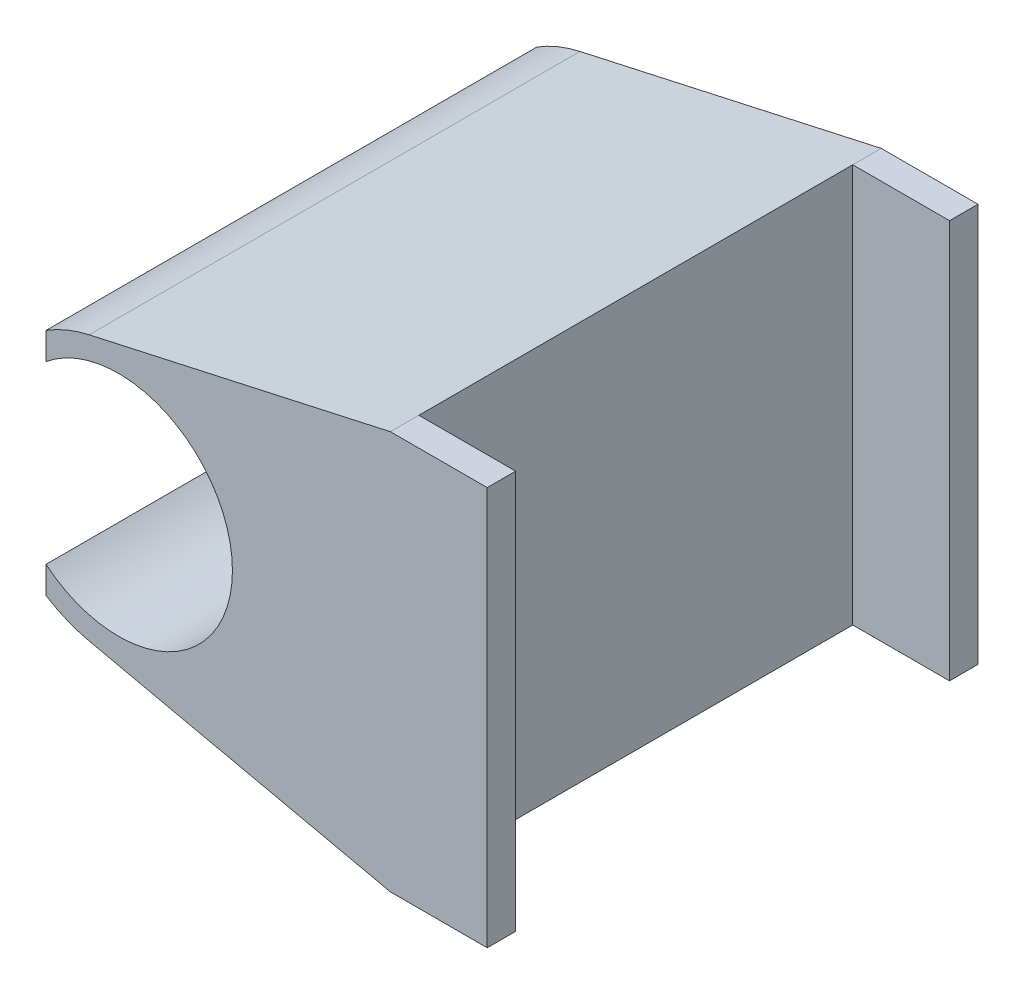
SolidWorks part; units mm, degrees
ref_plane "Front Plane" through (0, 0, 0) normal (0, 0, 1) x (1, 0, 0)
ref_plane "Top Plane" through (0, 0, 0) normal (0, 1, 0) x (1, 0, 0)
ref_plane "Right Plane" through (0, 0, 0) normal (1, 0, 0) x (0, 0, -1)
sketch "Sketch1" plane through (0, 0, 0) normal (0, 1, 0) x (1, 0, 0)
  line L0 (0, 26.772) -> (0, 29.272)
  line L5 (0, 29.272) -> (-42.375, 29.272)
  line L6 (-42.375, 29.272) -> (-42.375, -13.828)
  line L11 (-42.375, -13.828) -> (0, -13.828)
  line L12 (0, -13.828) -> (0, -11.328)
  line L13 (0, -11.328) -> (-8.5, -11.328)
  line L14 (-8.5, -11.328) -> (-8.5, 26.772)
  line L15 (-8.5, 26.772) -> (0, 26.772)
  dimension "D1" = 38.1
  dimension "D2" = 8.5
  dimension "D3" = 2.5
  dimension "D4" = 2.5
  dimension "D5" = 33.875
extrude "Boss-Extrude1" add sketch "Sketch1" along normal blind 35
sketch "Sketch2" plane through (0, 0, 13.828) normal (0, 0, 1) x (1, 0, 0)
  line L0 (-42.375, 7.5) -> (-8.5, 0)
  line L1 (-42.375, 7.5) -> (-42.375, 0)
  line L2 (-42.375, 35) -> (-42.375, 0) construction
  line L3 (0, 17.5) -> (-42.375, 17.5) construction
  line L4 (0, 35) -> (0, 0) construction
  line L5 (-42.375, 0) -> (0, 0) construction
  line L6 (-42.375, 0) -> (-8.5, 0)
  line L7 (-42.375, 27.5) -> (-42.375, 35)
  line L8 (-42.375, 27.5) -> (-8.5, 35)
  line L9 (-42.375, 35) -> (-8.5, 35)
  line L10 (-42.375, 27.5) -> (-42.375, 7.5)
  line L16 (-45.203, 6.6966) -> (-38.7462, 6.6966)
  line L17 (-45.203, 6.6966) -> (-45.203, 28.3034)
  line L18 (-45.203, 28.3034) -> (-38.7462, 28.3034)
  line L19 (-38.7462, 6.6966) -> (-38.7462, 28.3034)
  line L20 (-45.203, 6.6966) -> (-38.7462, 28.3034) construction
  line L21 (-45.203, 28.3034) -> (-38.7462, 6.6966) construction
  circle A0 centre (-32.375, 17.5) radius 11.9252
  circle A1 centre (-32.375, 17.5) radius 10
  point P8 (-32.375, 7.5)
  point P22 (-41.9746, 17.5)
  line M11 (-42.375, 0) -> (0, 0)
  line M13 (0, 35) -> (-42.375, 35)
  line M14 (-42.375, 35) -> (-42.375, 0)
  dimension "D3" = 10
  dimension "D1" = 0
extrude "Cut-Extrude1" cut sketch "Sketch2" against normal through all contours L16 L1 L0 M11 | L16 L0 M14 | A0 L0 L19 M14 | A0 L19 L0 | L18 L8 M14 M13 | A0 L8 L19 | L18 L7 L8 | A0 L19 L8 M14 | L19 A1 | L19 A1 | A1 L19 A0 L10 | A1 A0 L19 M14
